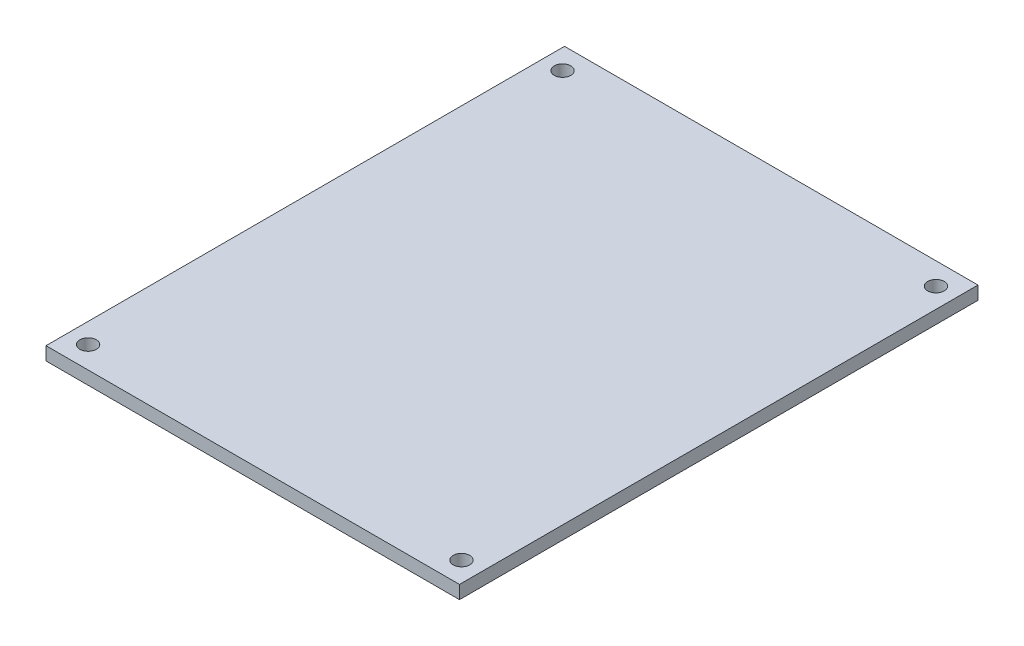
SolidWorks part; units mm, degrees
ref_plane "Front Plane" through (0, 0, 0) normal (0, 0, 1) x (1, 0, 0)
ref_plane "Top Plane" through (0, 0, 0) normal (0, 1, 0) x (1, 0, 0)
ref_plane "Right Plane" through (0, 0, 0) normal (1, 0, 0) x (0, 0, -1)
sketch "Sketch1" plane through (0, 0, 0) normal (0, 1, 0) x (1, 0, 0)
  line L0 (-22.9362, 29.1465) -> (22.9362, 29.1465) construction
  line L1 (-25.4, 31.8516) -> (25.4, 31.8516)
  line L2 (-25.4, 31.8516) -> (-25.4, -31.8516)
  line L3 (-25.4, -31.8516) -> (25.4, -31.8516)
  line L4 (25.4, 31.8516) -> (25.4, -31.8516)
  line L5 (22.9362, 29.1465) -> (22.9362, -29.1465) construction
  circle A0 centre (-22.9362, 29.1465) radius 1.016
  circle A1 centre (22.9362, 29.1465) radius 1.016
  circle A2 centre (22.9362, -29.1465) radius 1.016
  circle A3 centre (-22.9362, -29.1465) radius 1.016
  point P4 (25.4, 0)
  point P5 (0, 31.8516)
  point P6 (-22.9362, 29.1465)
  point P7 (0, 0)
  point P8 (22.9362, 29.1465)
  point P12 (0, 29.1465)
  point P15 (22.9362, 0)
  dimension "D4" = 2.032
  dimension "D1" = 63.7032
  dimension "D2" = 50.8
  dimension "D3" = 45.8724
  dimension "D5" = 58.293
extrude "Boss-Extrude1" add sketch "Sketch1" along normal blind 1.6256
